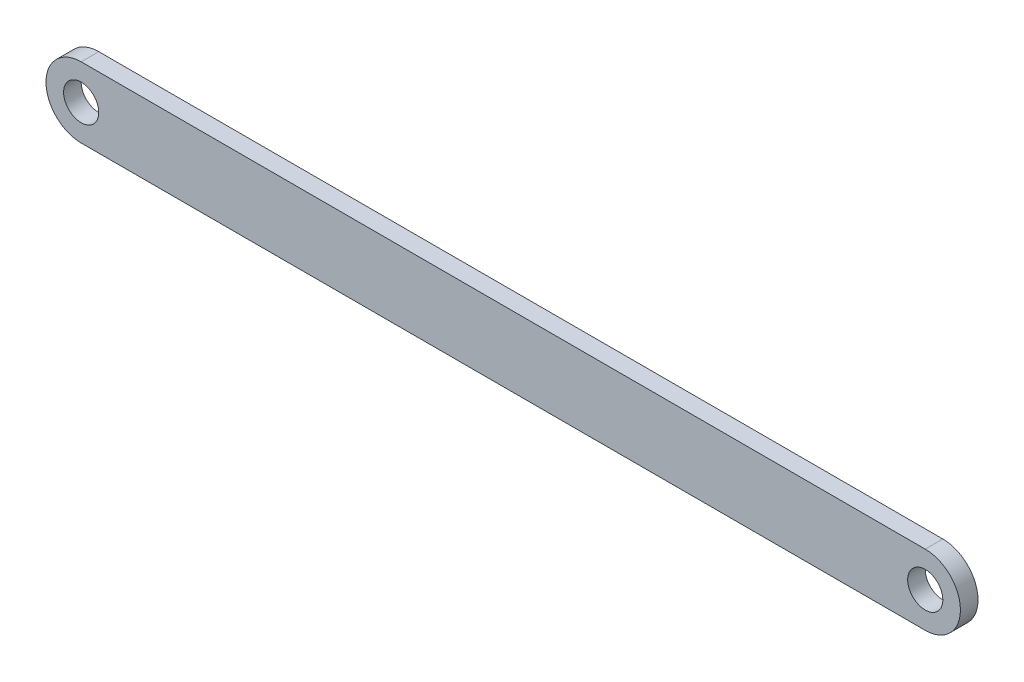
SolidWorks part; units mm, degrees
material "1060 Alloy"
ref_plane "Front Plane" through (0, 0, 0) normal (0, 0, 1) x (1, 0, 0)
ref_plane "Top Plane" through (0, 0, 0) normal (0, 1, 0) x (1, 0, 0)
ref_plane "Right Plane" through (0, 0, 0) normal (1, 0, 0) x (0, 0, -1)
sketch "Sketch1" plane through (0, 0, 0) normal (0, 0, 1) x (1, 0, 0)
  line L0 (-710.9896, 0.1574) -> (49289.0104, 0.1574) construction
  line L1 (0, 0) -> (0, 71.3201) construction
  line L2 (-762, 63.6574) -> (762, 63.6574)
  line L3 (-762, -63.3426) -> (762, -63.3426)
  arc A0 (-762, 63.6574) -> (-762, -63.3426) centre (-762, 0.1574) ccw
  arc A1 (762, -63.3426) -> (762, 63.6574) centre (762, 0.1574) ccw
  circle A2 centre (-762, 0.1574) radius 31.75
  circle A3 centre (762, 0.1574) radius 31.75
  dimension "D2" = 63.5
  dimension "D3" = 63.5
  dimension "D1" = 1524
extrude "Boss-Extrude1" add sketch "Sketch1" along normal mid plane 31.75
